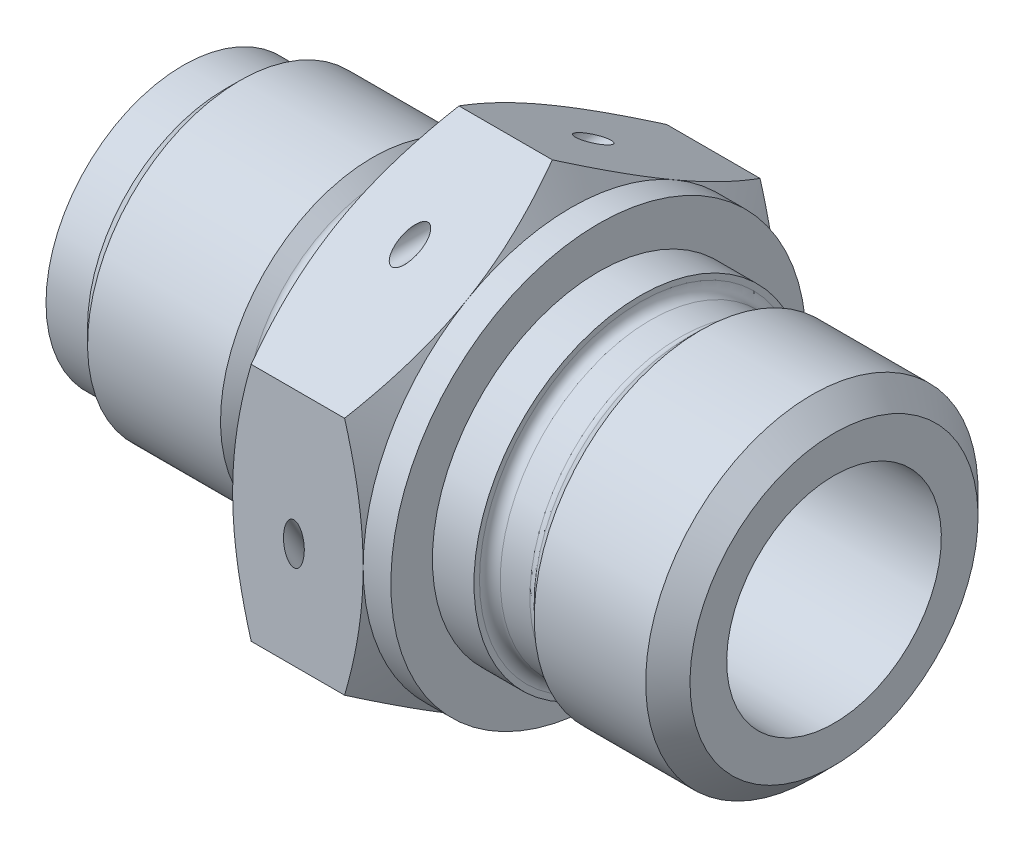
SolidWorks part; units mm, degrees
material "Алюминиевая бронза"
ref_plane "Спереди" through (0, 0, 0) normal (0, 0, 1) x (1, 0, 0)
ref_plane "Сверху" through (0, 0, 0) normal (0, 1, 0) x (1, 0, 0)
ref_plane "Справа" through (0, 0, 0) normal (1, 0, 0) x (0, 0, -1)
sketch "Эскиз1" plane through (0, 0, 0) normal (0, 0, 1) x (1, 0, 0)
  line L0 (0, 0) -> (-292.1333, 0) construction
  line L1 (0, 7.75) -> (-19.3, 7.75)
  line L2 (-19.3, 7.75) -> (-19.3, 3)
  line L3 (-19.3, 3) -> (-50, 3)
  line L4 (-50, 3) -> (-50, 4.75)
  line L5 (-49.75, 5) -> (-47, 5)
  line L6 (-47, 5) -> (-47, 9.9)
  line L7 (-47, 9.9) -> (-44, 9.9)
  line L8 (-44, 9.9) -> (-42.9, 11)
  line L9 (-42.9, 11) -> (-33.3, 11)
  line L10 (-33.3, 11) -> (-32.4197, 10.1197)
  line L11 (-31.8893, 9.9) -> (-29.75, 9.9)
  line L12 (-29, 10.65) -> (-29, 20)
  line L13 (-29, 20) -> (-19, 20)
  line L14 (-19, 20) -> (-19, 15)
  line L15 (-17, 12) -> (-14, 12)
  line L16 (-14, 12) -> (-14, 11.6)
  line L17 (-13.25, 10.85) -> (-11.1107, 10.85)
  line L18 (-10.5803, 11.0697) -> (-9.65, 12)
  line L19 (-9.65, 12) -> (-1.6, 12)
  line L20 (-1.6, 12) -> (0, 10.4)
  line L21 (0, 10.4) -> (0, 7.75)
  line L22 (-19, 15) -> (-17, 15)
  line L23 (-17, 15) -> (-17, 12)
  line L24 (-50, 4.75) -> (-49.75, 5)
  arc A0 (-29.75, 9.9) -> (-29, 10.65) centre (-29.75, 10.65) ccw
  arc A1 (-32.4197, 10.1197) -> (-31.8893, 9.9) centre (-31.8893, 10.65) ccw
  arc A2 (-11.1107, 10.85) -> (-10.5803, 11.0697) centre (-11.1107, 11.6) ccw
  arc A3 (-14, 11.6) -> (-13.25, 10.85) centre (-13.25, 11.6) ccw
  point P8 (-50, 5)
  point P28 (-29, 9.9)
  point P31 (-32.2, 9.9)
  point P34 (-10.8, 10.85)
  point P37 (-14, 10.85)
  dimension "D24" = 0.75
  dimension "D1" = 15.5
  dimension "D2" = 6
  dimension "D3" = 19.3
  dimension "D4" = 3
  dimension "D5" = 3
  dimension "d 1" = 10
  dimension "d 2" = 19.8
  dimension "d" = 22
  dimension "D9" = 45
  dimension "D10" = 45
  dimension "D11" = 1.6
  dimension "D12" = 24
  dimension "D13" = 21.7
  dimension "D14" = 3.2
  dimension "D15" = 17
  dimension "D16" = 14
  dimension "l" = 18
  dimension "D18" = 3.2
  dimension "D19" = 30
  dimension "D20" = 40
  dimension "L'" = 50
  dimension "D22" = 19
  dimension "D23" = 24
  dimension "D25" = 0.25
  dimension "D26" = 45
revolve "Повернуть1" add sketch "Эскиз1" angle 360 about L0
cosmetic thread "Условное изображение резьбы1" parameters "D2"=20.344
cosmetic thread "Условное изображение резьбы2" parameters "D2"=20.704
cosmetic thread "Условное изображение резьбы3" [suppressed] parameters "D2"=24.797
sketch "Эскиз2" plane through (-29, 0, 0) normal (-1, 0, 0) x (0, 0, 1)
  line L1 (0, 17.3205) -> (-15, 8.6603)
  line L2 (-15, 8.6603) -> (-15, -8.6603)
  line L3 (-15, -8.6603) -> (0, -17.3205)
  line L4 (0, -17.3205) -> (15, -8.6603)
  line L5 (15, -8.6603) -> (15, 8.6603)
  line L6 (15, 8.6603) -> (0, 17.3205)
  circle A0 centre (0, 0) radius 15 construction
  dimension "D1" = 30
extrude "Вырез-Вытянуть1" cut sketch "Эскиз2" against normal through all flip side to cut
sketch "Эскиз3" plane through (-19, 0, 0) normal (1, 0, 0) x (0, 0, -1)
  circle A0 centre (0, 0) radius 15 construction
  circle A1 centre (0, 0) radius 15
extrude "Вырез-Вытянуть2" cut sketch "Эскиз3" against normal through all draft 60 flip side to cut
sketch "Эскиз4" plane through (-29, 0, 0) normal (-1, 0, 0) x (0, 0, 1)
  circle A2 centre (0, 0) radius 14
  dimension "D1" = 28
extrude "Вырез-Вытянуть3" cut sketch "Эскиз4" against normal through all draft 60 flip side to cut
sketch "Эскиз5" plane through (0, 0, 0) normal (0, 0, 1) x (1, 0, 0)
  line L0 (-29, 14) -> (-29, -14) construction
  circle A0 centre (-24, 13.5) radius 0.75
  dimension "D2" = 1.5
  dimension "D1" = 5
  dimension "D3" = 13.5
extrude "Вырез-Вытянуть4" cut sketch "Эскиз5" against normal through all and the other way through all
pattern_circular "Круговой массив1" count 3 over 360 about axis through (0, 0, 0) along (1, 0, 0) of "Вырез-Вытянуть4"
